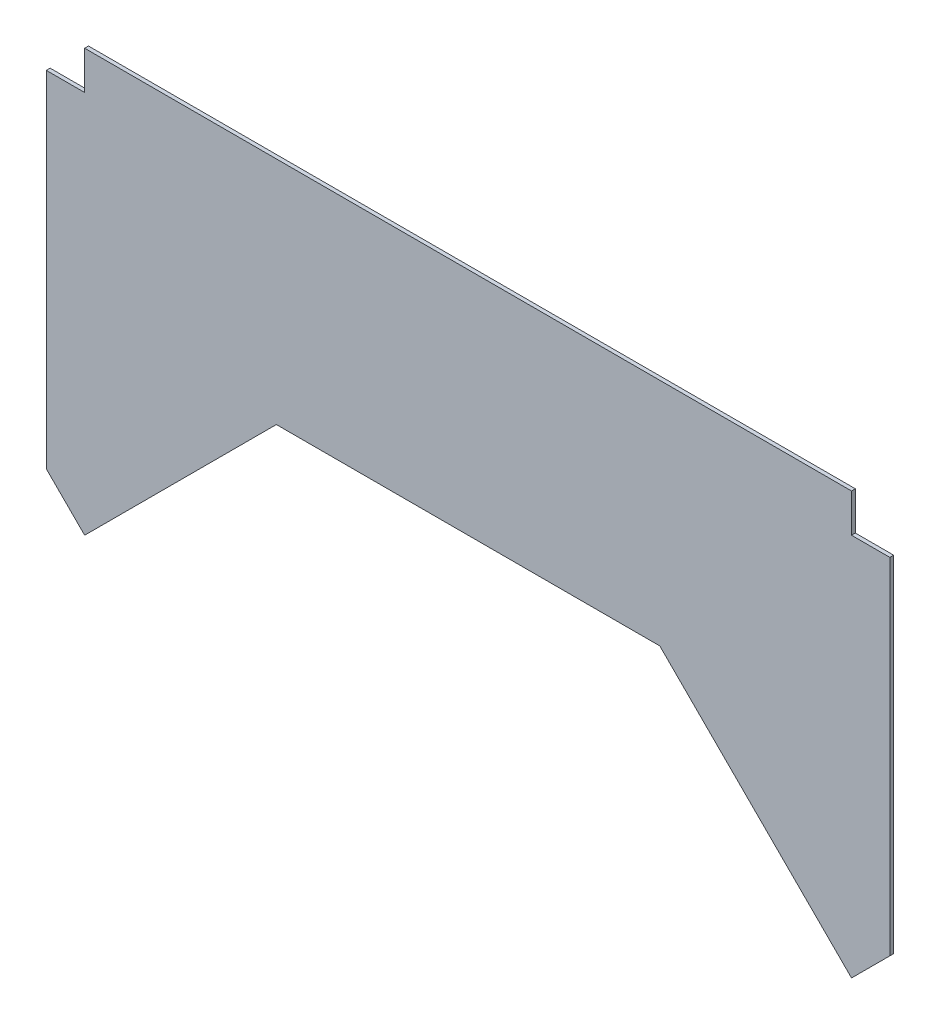
SolidWorks part; units mm, degrees
ref_plane "Front" through (0, 0, 0) normal (0, 0, 1) x (1, 0, 0)
ref_plane "Top" through (0, 0, 0) normal (0, 1, 0) x (1, 0, 0)
ref_plane "Right" through (0, 0, 0) normal (1, 0, 0) x (0, 0, -1)
sketch "Croquis1" plane through (0, 0, 0) normal (0, 0, 1) x (1, 0, 0)
  line L0 (110, 0) -> (100, 0)
  line L2 (50, 0) -> (-50, 0) construction
  line L3 (100, 0) -> (100, -100) construction
  line L4 (50, 0) -> (50, -50) construction
  line L5 (100, -100) -> (50, -50)
  line L8 (0, 0) -> (0, -120.7107) construction
  line L9 (110, 0) -> (110, -90)
  line L10 (110, -90) -> (100, -100)
  line L11 (-50, 0) -> (-50, -50) construction
  line L12 (-100, 0) -> (-100, -100) construction
  line L13 (-110, -90) -> (-100, -100)
  line L14 (-110, 0) -> (-110, -90)
  line L16 (-100, -100) -> (-50, -50)
  line L17 (-100, 0) -> (-50, 0) construction
  line L18 (-110, 0) -> (-100, 0)
  line L19 (-50, -50) -> (50, -50)
  line L20 (-100, 0) -> (-100, 10)
  line L21 (-100, 10) -> (100, 10)
  line L22 (100, 10) -> (100, 0)
  circle A0 centre (50, -50) radius 70.7107 construction
  circle A1 centre (-50, -50) radius 70.7107 construction
  dimension "D1" = 50
  dimension "D2" = 50
  dimension "D3" = 90
  dimension "D4" = 10
  dimension "D5" = 50
  dimension "D6" = 100
  dimension "D7" = 10
extrude "Saliente-Extruir1" add sketch "Croquis1" along normal blind 1
